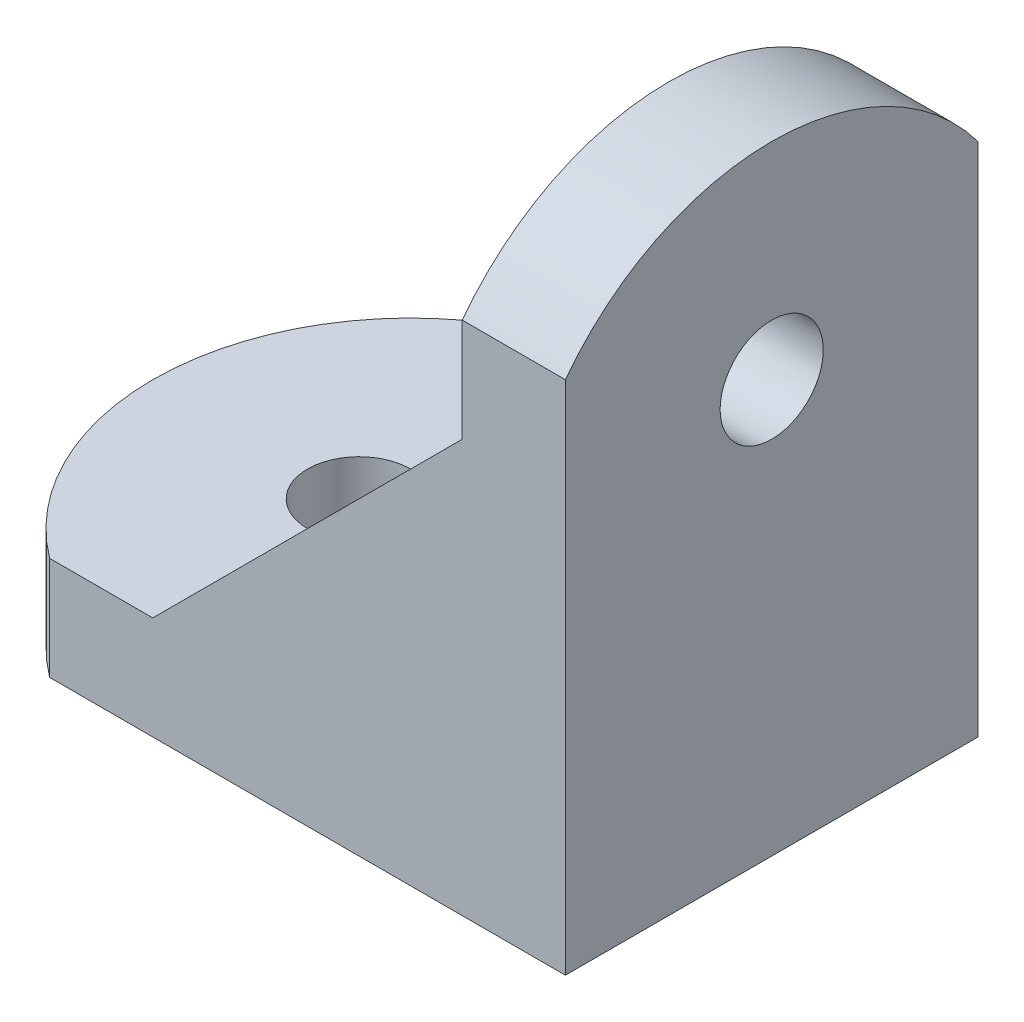
SolidWorks part; units mm, degrees
ref_plane "Front Plane" through (0, 0, 0) normal (0, 0, 1) x (1, 0, 0)
ref_plane "Top Plane" through (0, 0, 0) normal (0, 1, 0) x (1, 0, 0)
ref_plane "Right Plane" through (0, 0, 0) normal (1, 0, 0) x (0, 0, -1)
sketch "Sketch2" plane through (0, 0, 0) normal (0, 1, 0) x (1, 0, 0)
  line L1 (-21.9992, 47.4852) -> (8.0008, 47.4852)
  line L2 (-21.9992, 47.4852) -> (-21.9992, 27.4852)
  line L3 (-21.9992, 27.4852) -> (8.0008, 27.4852)
  line L4 (8.0008, 47.4852) -> (8.0008, 27.4852)
extrude "Boss-Extrude1" add sketch "Sketch2" along normal blind 30
sketch "Sketch3" plane through (0, 30, 0) normal (0, 1, 0) x (1, 0, 0)
  line L0 (-21.9992, 47.4852) -> (-21.9992, 42.4852)
  line L1 (-21.9992, 47.4852) -> (-21.9992, 27.4852) construction
  line L2 (-21.9992, 42.4852) -> (3.0008, 42.4852)
  line L3 (3.0008, 42.4852) -> (3.0008, 32.4852)
  line L4 (3.0008, 32.4852) -> (-21.9992, 32.4852)
  line L5 (-21.9992, 32.4852) -> (-21.9992, 42.4852)
  line M5 (-21.9992, 47.4852) -> (-21.9992, 27.4852)
extrude "Cut-Extrude1" cut sketch "Sketch3" against normal blind 25 contours L4 L3 L2 M5
sketch "Sketch4" plane through (0, 0, -47.4852) normal (0, 0, -1) x (-1, 0, 0)
  line L0 (-8.0008, 30) -> (-3.0008, 30)
  line L1 (-8.0008, 30) -> (21.9992, 30) construction
  line L2 (21.9992, 0) -> (21.9992, 5)
  line L3 (21.9992, 30) -> (21.9992, 0) construction
  line L5 (-3.0008, 30) -> (21.9992, 30)
  line L6 (21.9992, 30) -> (21.9992, 5)
  line L7 (-3.0008, 30) -> (-3.0008, 0)
  line L8 (-8.0008, 0) -> (21.9992, 0) construction
  line L9 (21.9992, 5) -> (-3.0008, 5)
  line L10 (-3.0008, 30) -> (-3.0008, 20)
  line L11 (21.9992, 5) -> (11.9992, 5)
  line L12 (11.9992, 5) -> (-3.0008, 20)
  line L13 (-3.0008, 30) -> (21.9992, 30)
  line L14 (21.9992, 5) -> (21.9992, 30)
  line M2 (21.9992, 0) -> (21.9992, 30)
  line M3 (21.9992, 30) -> (-8.0008, 30)
extrude "Cut-Extrude3" cut sketch "Sketch4" against normal blind 25 contours L12 L9 L7 M2 M3
sketch "Sketch5" plane through (8.0008, 0, 0) normal (1, 0, 0) x (0, 0, -1)
  line L0 (27.4852, 30) -> (27.4852, 25)
  line L1 (27.4852, 30) -> (47.4852, 30)
  line L2 (27.4852, 30) -> (27.4852, 0)
  line L3 (27.4852, 0) -> (47.4852, 0)
  line L4 (47.4852, 30) -> (47.4852, 0)
  line L5 (27.4852, 25) -> (47.4852, 25)
  arc A0 (27.4852, 25) -> (47.4852, 25) centre (37.4852, 17.5) cw
  line M9 (47.4852, 30) -> (27.4852, 30)
  line M10 (27.4852, 30) -> (27.4852, 0)
extrude "Cut-Extrude4" cut sketch "Sketch5" against normal blind 25 contours A0 L1 M10 | A0 L4 M9
sketch "Sketch6" plane through (0, 0, 0) normal (0, -1, 0) x (1, 0, 0)
  line L0 (-21.9992, -27.4852) -> (-16.9992, -27.4852)
  line L1 (-21.9992, -27.4852) -> (8.0008, -27.4852)
  line L2 (-21.9992, -27.4852) -> (-21.9992, -47.4852)
  line L3 (-21.9992, -47.4852) -> (8.0008, -47.4852)
  line L4 (8.0008, -27.4852) -> (8.0008, -47.4852)
  line L5 (-21.9992, -47.4852) -> (-16.9992, -47.4852)
  arc A0 (-16.9992, -27.4852) -> (-16.9992, -47.4852) centre (-9.4992, -37.4852) ccw
  line M5 (-21.9992, -27.4852) -> (-21.9992, -47.4852)
  line M6 (-21.9992, -47.4852) -> (8.0008, -47.4852)
  line M8 (8.0008, -27.4852) -> (-21.9992, -27.4852)
extrude "Cut-Extrude5" cut sketch "Sketch6" against normal blind 25 contours A0 M8 M5 | A0 L2 M6
sketch "Sketch7" plane through (0, 5, 0) normal (0, 1, 0) x (1, 0, 0)
  circle A0 centre (-11.9992, 37.4852) radius 2.5
extrude "Cut-Extrude6" cut sketch "Sketch7" against normal blind 25 contours A0
sketch "Sketch8" plane through (3.0008, 0, 0) normal (-1, 0, 0) x (0, 0, 1)
  circle A0 centre (-37.4852, 20) radius 2.5
extrude "Cut-Extrude7" cut sketch "Sketch8" against normal blind 25 contours A0
